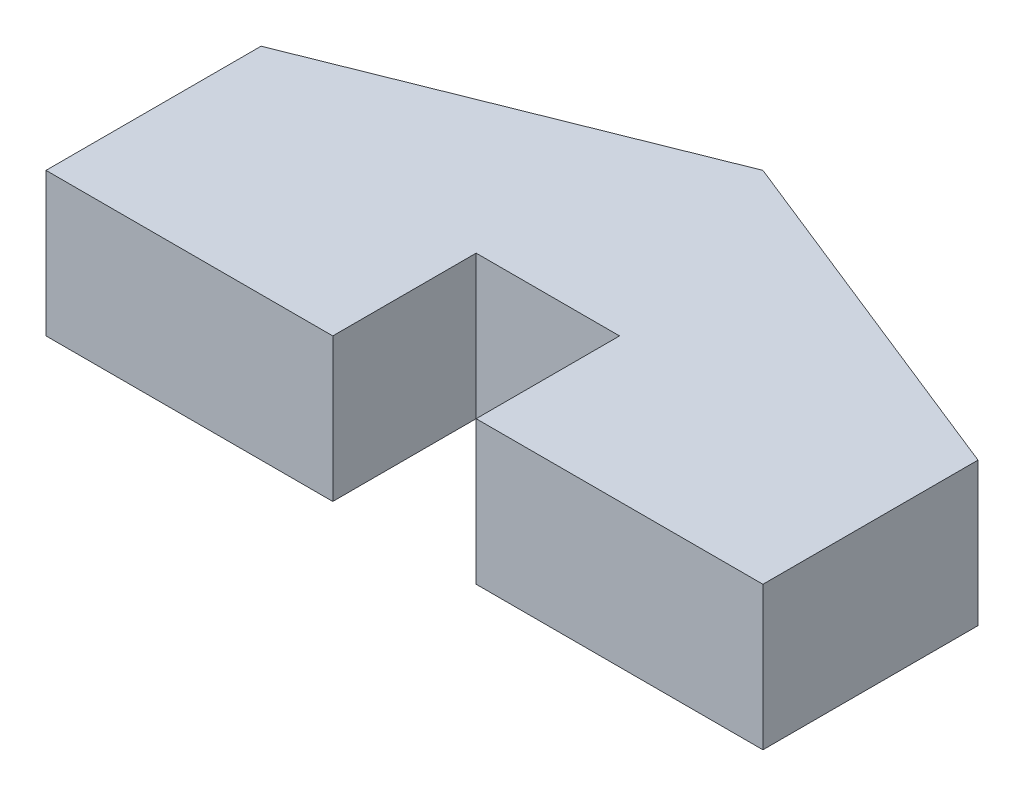
SolidWorks part; units mm, degrees
ref_plane "Front Plane" through (0, 0, 0) normal (0, 0, 1) x (1, 0, 0)
ref_plane "Top Plane" through (0, 0, 0) normal (0, 1, 0) x (1, 0, 0)
ref_plane "Right Plane" through (0, 0, 0) normal (1, 0, 0) x (0, 0, -1)
sketch "Sketch1" plane through (0, 0, 0) normal (0, 1, 0) x (1, 0, 0)
  line L0 (60, 0) -> (60, 20)
  line L1 (50, 20) -> (50, 50) construction
  line L2 (0, 0) -> (40, 0)
  line L3 (0, 0) -> (0, 30)
  line L5 (100, 0) -> (100, 30)
  line L6 (50, 50) -> (0, 30)
  line L7 (50, 50) -> (100, 30)
  line L10 (60, 20) -> (40, 20)
  line L11 (40, 0) -> (40, 20)
  line L12 (60, 0) -> (100, 0)
  dimension "D1" = 100
  dimension "D2" = 30
  dimension "D3" = 53.8516
  dimension "D4" = 10
  dimension "D5" = 20
extrude "Boss-Extrude1" add sketch "Sketch1" along normal blind 20
